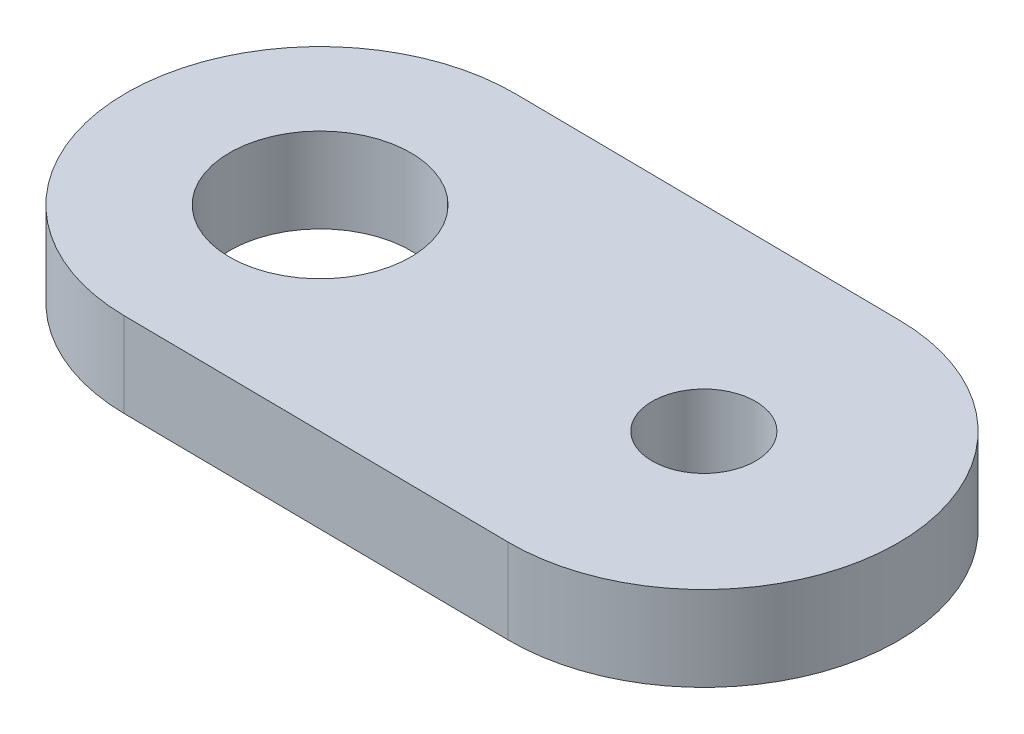
SolidWorks part; units mm, degrees
ref_plane "Front Plane" through (0, 0, 0) normal (0, 0, 1) x (1, 0, 0)
ref_plane "Top Plane" through (0, 0, 0) normal (0, 1, 0) x (1, 0, 0)
ref_plane "Right Plane" through (0, 0, 0) normal (1, 0, 0) x (0, 0, -1)
sketch "Sketch1" plane through (0, -82.5, 0) normal (0, 1, 0) x (1, 0, 0)
  line L0 (-105, -60) -> (-90, -60.1593) construction
  line L1 (-104.9204, -52.5004) -> (-89.9204, -52.6597)
  line L2 (-105.0796, -67.4996) -> (-90.0796, -67.6588)
  arc A0 (-104.9204, -52.5004) -> (-105.0796, -67.4996) centre (-105, -60) ccw
  arc A1 (-90.0796, -67.6588) -> (-89.9204, -52.6597) centre (-90, -60.1593) ccw
  circle A2 centre (-105, -60) radius 3.5
  circle A3 centre (-90, -60.1593) radius 2
  ellipse E0 centre (-90, -60.1593) end of major axis (-88, -60.1593) minor radius 1.9999 construction
  point P3 (-97.5, -60.0796)
  dimension "D1" = 7
  dimension "D3" = 4
  dimension "D2" = 15
extrude "Boss-Extrude1" add sketch "Sketch1" along normal up to vertex (3.2782 mm away)
